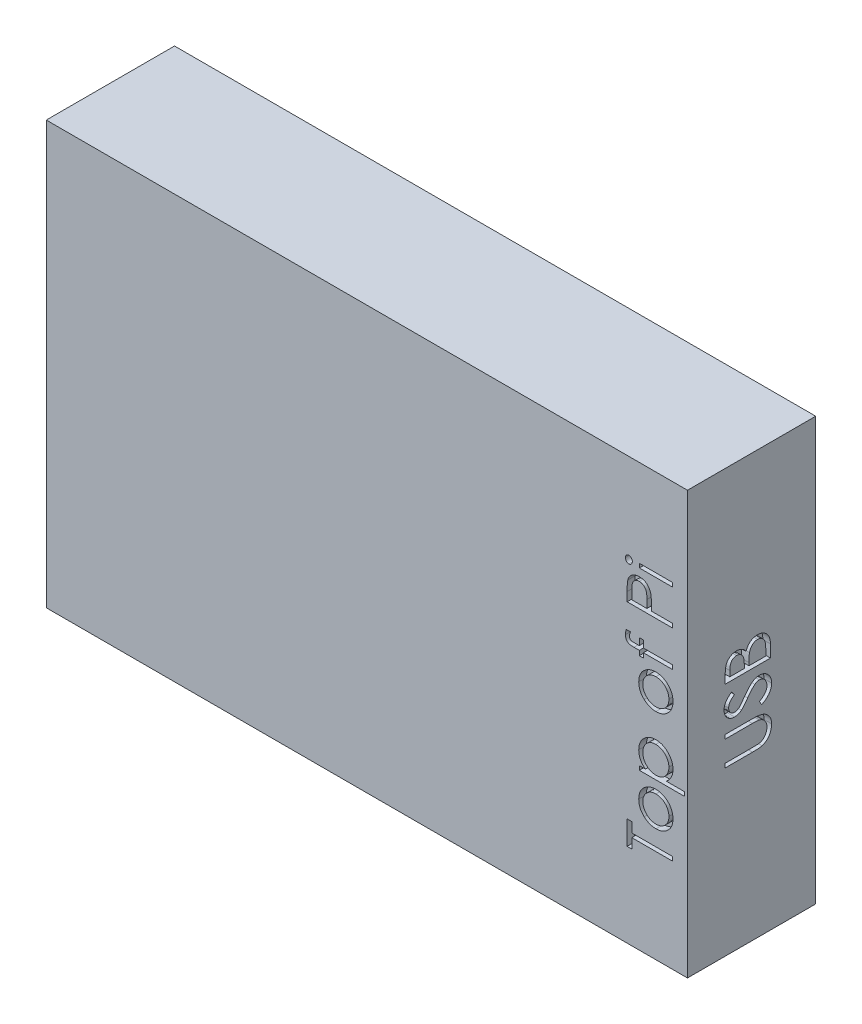
SolidWorks part; units mm, degrees
ref_plane "Front Plane" through (0, 0, 0) normal (0, 0, 1) x (1, 0, 0)
ref_plane "Top Plane" through (0, 0, 0) normal (0, 1, 0) x (1, 0, 0)
ref_plane "Right Plane" through (0, 0, 0) normal (1, 0, 0) x (0, 0, -1)
sketch "Sketch1" plane through (0, 0, 0) normal (0, 0, 1) x (1, 0, 0)
  line L1 (0, 0) -> (85, 0)
  line L2 (0, 0) -> (0, 56)
  line L3 (0, 56) -> (85, 56)
  line L4 (85, 0) -> (85, 56)
  dimension "D1" = 85
  dimension "D2" = 56
extrude "Boss-Extrude1" add sketch "Sketch1" along normal blind 17
sketch "Sketch2" plane through (85, 0, 0) normal (1, 0, 0) x (0, 0, -1)
  line L0 (-6, 0) -> (-6, 56) construction
  line L3 (0, 0) -> (0, 56) construction
  text T0 "USB" font "Century Gothic" height 6
  dimension "D1" = 6
extrude "Cut-Extrude1" cut sketch "Sketch2" against normal blind 1
sketch "Sketch3" plane through (0, 0, 17) normal (0, 0, 1) x (1, 0, 0)
  line L0 (83, 0) -> (83, 56) construction
  line L1 (0, 0) -> (85, 0) construction
  line L2 (85, 56) -> (0, 56) construction
  line L3 (85, 0) -> (85, 56) construction
  text T0 "Top of Pi" font "Century Gothic" height 6
  dimension "D1" = 2
extrude "Cut-Extrude2" cut sketch "Sketch3" against normal blind 1
